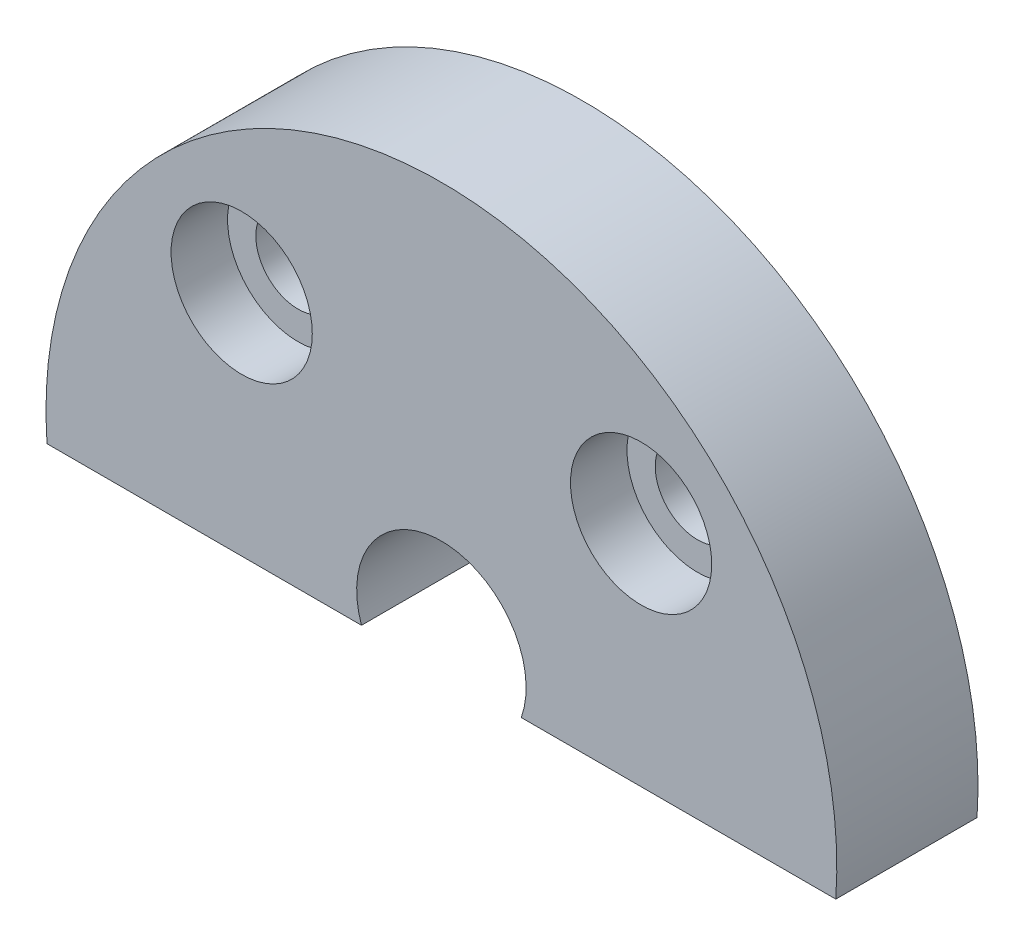
SolidWorks part; units mm, degrees
ref_plane "Plan de face" through (0, 0, 0) normal (0, 0, 1) x (1, 0, 0)
ref_plane "Plan de dessus" through (0, 0, 0) normal (0, 1, 0) x (1, 0, 0)
ref_plane "Plan de droite" through (0, 0, 0) normal (1, 0, 0) x (0, 0, -1)
sketch "Esquisse1" plane through (0, 0, 0) normal (0, 0, 1) x (1, 0, 0)
  line L0 (-13.9642, -1) -> (-2.8284, -1)
  line L1 (-7.0711, 7.0711) -> (7.0711, 7.0711) construction
  line L2 (-7.0711, 7.0711) -> (-7.0711, -7.0711) construction
  line L3 (2.8284, -1) -> (13.9642, -1)
  arc A0 (13.9642, -1) -> (-13.9642, -1) centre (0, 0) ccw
  circle A1 centre (0, 0) radius 10 construction
  circle A2 centre (-7.0711, 7.0711) radius 1.5
  circle A3 centre (7.0711, 7.0711) radius 1.5
  arc A4 (2.8284, -1) -> (-2.8284, -1) centre (0, 0) ccw
  dimension "D1" = 28
  dimension "D3" = 20
  dimension "D4" = 3
  dimension "D5" = 6
  dimension "D2" = 1
extrude "Extrusion1" add sketch "Esquisse1" along normal blind 5
sketch "Esquisse2" plane through (0, 0, 5) normal (0, 0, 1) x (1, 0, 0)
  circle A0 centre (-7.0711, 7.0711) radius 2.5
  circle A1 centre (7.0711, 7.0711) radius 2.5
  circle A2 centre (-7.0711, 7.0711) radius 1.5 construction
  circle A3 centre (7.0711, 7.0711) radius 1.5 construction
  dimension "D1" = 5
extrude "Extrusion2" cut sketch "Esquisse2" against normal blind 2
